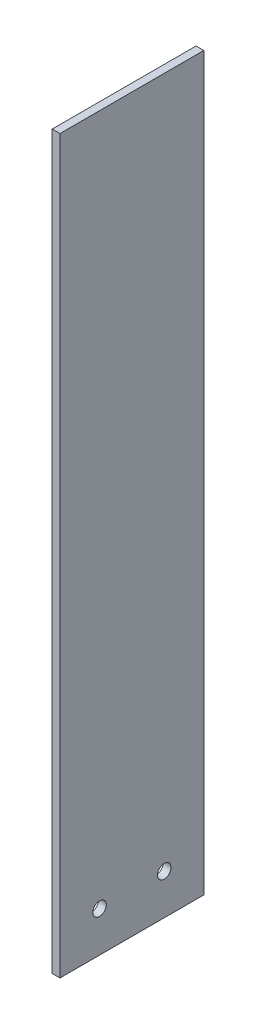
SolidWorks part; units mm, degrees
ref_plane "Front Plane" through (0, 0, 0) normal (0, 0, 1) x (1, 0, 0)
ref_plane "Top Plane" through (0, 0, 0) normal (0, 1, 0) x (1, 0, 0)
ref_plane "Right Plane" through (0, 0, 0) normal (1, 0, 0) x (0, 0, -1)
sketch "Sketch1" plane through (0, 0, 0) normal (1, 0, 0) x (0, 0, -1)
  line L1 (-28.2194, 143.51) -> (28.2194, 143.51)
  line L2 (-28.2194, 143.51) -> (-28.2194, -143.51)
  line L3 (-28.2194, -143.51) -> (28.2194, -143.51)
  line L4 (28.2194, 143.51) -> (28.2194, -143.51)
  line L5 (-28.2194, 143.51) -> (28.2194, -143.51) construction
  line L6 (-28.2194, -143.51) -> (28.2194, 143.51) construction
  point P0 (0, 0)
  dimension "D1" = 56.4388
  dimension "D2" = 287.02
extrude "Boss-Extrude1" add sketch "Sketch1" along normal blind 3.048
sketch "Sketch2" plane through (3.048, 0, 0) normal (1, 0, 0) x (0, 0, -1)
  line L0 (0, 143.51) -> (0, -143.51) construction
  line L1 (28.2194, 143.51) -> (-28.2194, 143.51) construction
  line L2 (-28.2194, -143.51) -> (28.2194, -143.51) construction
  point P0 (-12.7, -127.7112)
  point P8 (0, 0)
  point P9 (12.7, -127.7112)
  dimension "D1" = 12.7
  dimension "D2" = 15.7988
hole_wizard "#4 (0.209) Diameter Hole1" positions "Sketch3" profile "Sketch4" hole size "#4" standard "ANSI Inch" end condition through all
sketch "Sketch3" plane through (3.048, 0, 0) normal (1, 0, 0) x (0, 0, -1)
  point P0 (-12.7, -127.7112)
  point P3 (12.7, -127.7112)
sketch "Sketch4" plane through (3.048, -127.7112, 12.7) normal (0, 1, 0) x (0, 0, -1)
  line L0 (0, 0) -> (0, 3.048)
  line L1 (0, 3.048) -> (2.6543, 3.048)
  line L2 (2.6543, 3.048) -> (2.6543, 0)
  line L5 (2.6543, 0) -> (0, 0)
  line L11 (0, -6.35) -> (0, 107.95) construction
  dimension "Thru Hole Dia." = 5.3086
  dimension "Thru Hole Depth" = 3.048
equation "\"motor offset\"=6mm"
equation "\"thickness0.25\"=0.225in"
equation "\"thickness0.125\"=0.122in"
equation "\"thickness_acrylic0.1\"= 0.1in"
equation "\"D1@Sketch1\"=\"thickness_acrylic0.1\"+\"thickness0.125\"+2"
equation "\"D2@Sketch2\"=\"thickness0.125\" + 0.5"
